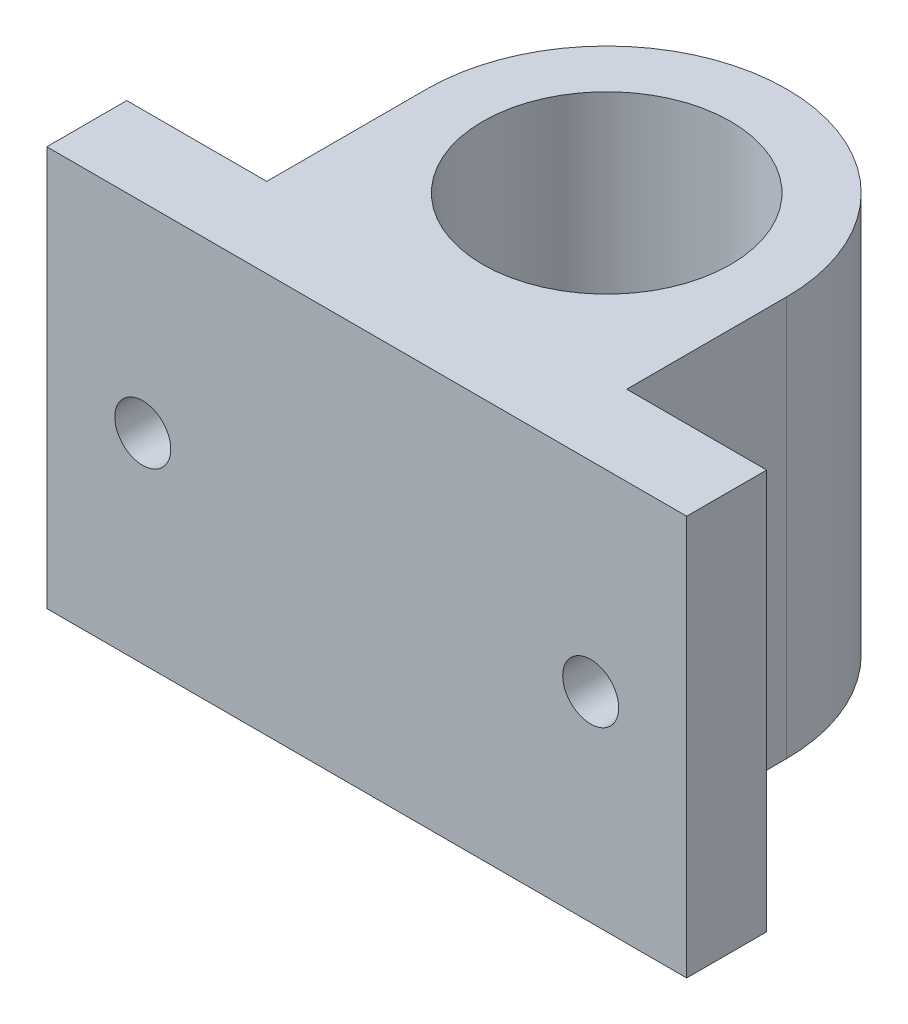
SolidWorks part; units mm, degrees
ref_plane "前视基准面" through (0, 0, 0) normal (0, 0, 1) x (1, 0, 0)
ref_plane "上视基准面" through (0, 0, 0) normal (0, 1, 0) x (1, 0, 0)
ref_plane "右视基准面" through (0, 0, 0) normal (1, 0, 0) x (0, 0, -1)
sketch "草图1" plane through (0, 0, 0) normal (0, 1, 0) x (1, 0, 0)
  line L0 (21.3441, -3.8871) -> (21.3441, -2.6855) construction
  line L1 (1.3441, 1.1129) -> (10.0941, 1.1129)
  line L2 (1.3441, 1.1129) -> (1.3441, -3.8871)
  line L3 (1.3441, -3.8871) -> (41.3441, -3.8871)
  line L4 (41.3441, 1.1129) -> (41.3441, -3.8871)
  line L5 (1.3441, 1.1129) -> (14.7709, -0.5655) construction
  line L6 (1.3441, -3.8871) -> (17.2206, -1.9025) construction
  line L7 (10.0941, 11.1129) -> (10.0941, 1.1129)
  line L8 (32.5941, 11.1129) -> (32.5941, 1.1129)
  line L9 (27.9172, -0.5655) -> (41.3441, 1.1129) construction
  line L10 (32.5941, 1.1129) -> (41.3441, 1.1129)
  circle A0 centre (21.3441, 11.1129) radius 7.75
  arc A2 (32.5941, 11.1129) -> (10.0941, 11.1129) centre (21.3441, 11.1129) ccw
  point P4 (21.3441, -1.3871)
  point P9 (0, 0)
  point P14 (0, 0)
  dimension "D3" = 15.5
  dimension "D4" = 10
  dimension "D1" = 5
  dimension "D2" = 40
extrude "凸台-拉伸1" add sketch "草图1" along normal blind 25
sketch "草图2" plane through (0, 0, -1.1129) normal (0, 0, -1) x (-1, 0, 0)
  line L0 (-41.3441, 12.5) -> (-1.3441, 12.5) construction
  line L1 (-41.3441, 25) -> (-41.3441, 0) construction
  line L2 (-1.3441, 25) -> (-1.3441, 0) construction
  circle A0 centre (-35.3441, 12.5) radius 1.75
  circle A1 centre (-7.3441, 12.5) radius 1.75
  point P10 (-21.3441, 12.5)
  dimension "D1" = 3.5
  dimension "D2" = 3.5
  dimension "D3" = 14
  dimension "D4" = 14
extrude "切除-拉伸1" cut sketch "草图2" against normal through all
sketch "草图3" plane through (0, 25, 0) normal (0, 1, 0) x (1, 0, 0)
